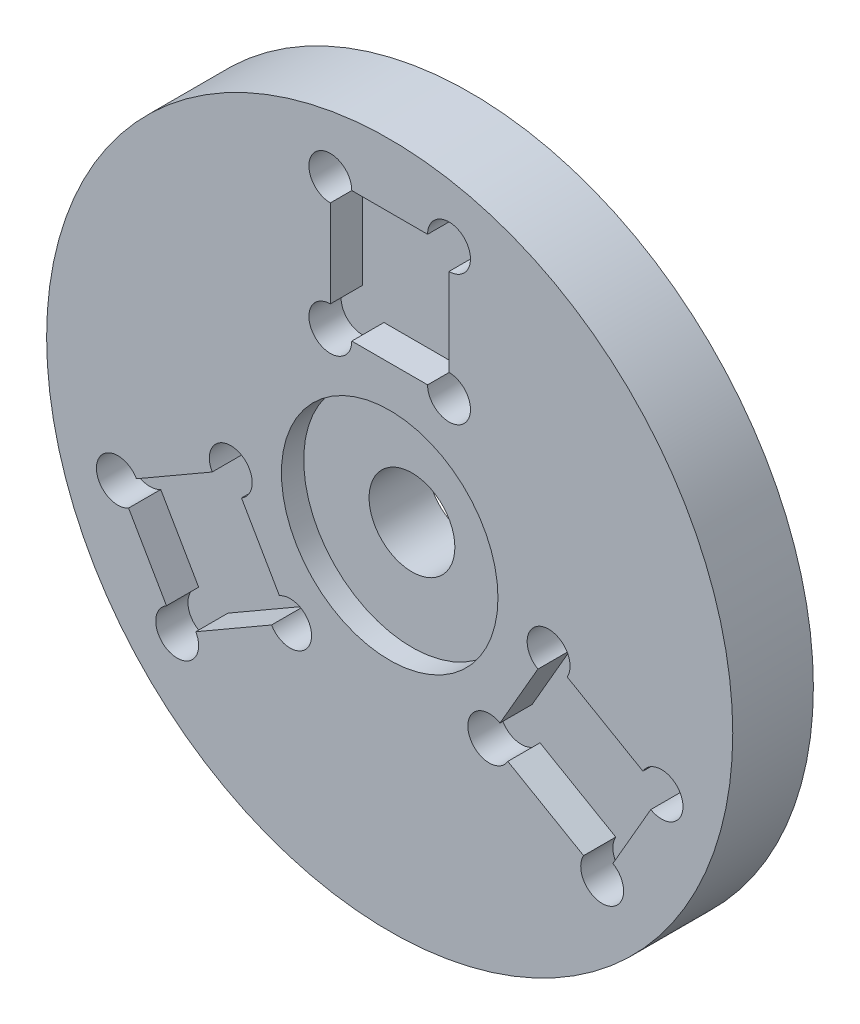
SolidWorks part; units mm, degrees
ref_plane "Front Plane" through (0, 0, 0) normal (0, 0, 1) x (1, 0, 0)
ref_plane "Top Plane" through (0, 0, 0) normal (0, 1, 0) x (1, 0, 0)
ref_plane "Right Plane" through (0, 0, 0) normal (1, 0, 0) x (0, 0, -1)
sketch "Sketch1" plane through (0, 0, 0) normal (0, 0, 1) x (1, 0, 0)
  circle A0 centre (0, 0) radius 50.8
  dimension "D1" = 101.6
extrude "baseplate" add sketch "Sketch1" along normal blind 11.938
sketch "coupling_circle" plane through (0, 0, 11.938) normal (0, 0, 1) x (1, 0, 0)
  circle A0 centre (0, 0) radius 31.75
  dimension "D1" = 63.5
sketch "Sketch3" plane through (0, 0, 11.938) normal (0, 0, 1) x (1, 0, 0)
  circle A0 centre (0, 0) radius 16.0337
  dimension "D1" = 32.0675
extrude "magnet_inset" cut sketch "Sketch3" against normal blind 3.302
sketch "Sketch4" plane through (0, 0, 11.938) normal (0, 0, 1) x (1, 0, 0)
  line L1 (-8.7877, 41.402) -> (8.7877, 41.402)
  line L2 (-8.7877, 41.402) -> (-8.7877, 22.098)
  line L3 (-8.7877, 22.098) -> (8.7877, 22.098)
  line L4 (8.7877, 41.402) -> (8.7877, 22.098)
  line L5 (-8.7877, 41.402) -> (8.7877, 22.098) construction
  line L6 (-8.7877, 22.098) -> (8.7877, 41.402) construction
  circle A0 centre (0, 0) radius 31.75 construction
  point P0 (0, 31.75)
  dimension "D1" = 19.304
  dimension "D2" = 17.5753
extrude "dowel_slot" cut sketch "Sketch4" against normal blind 4.7625
sketch "Sketch6" plane through (0, 0, 11.938) normal (0, 0, 1) x (1, 0, 0)
  circle A0 centre (-8.7877, 41.402) radius 3.175
  circle A1 centre (8.7877, 41.402) radius 3.175
  circle A2 centre (8.7877, 22.098) radius 3.175
  circle A3 centre (-8.7877, 22.098) radius 3.175
  dimension "D1" = 6.35
extrude "dowel_slot_reliefs" cut sketch "Sketch6" against normal up to surface (4.7625 mm away) up to face at (0, 31.75, 7.1755)
pattern_circular "dowel_slot_pattern" count 3 over 360 about axis through (0, 0, 0) along (0, 0, 1) of "dowel_slot", "dowel_slot_reliefs"
sketch "Sketch7" plane through (0, 0, 11.938) normal (0, 0, 1) x (1, 0, 0)
  circle A0 centre (0, 0) radius 6.35
  dimension "D1" = 12.7
extrude "central_hole" cut sketch "Sketch7" against normal through all
equation "\"plate_diam\"= 4"
equation "\"magnet_thickness\"= 0.125"
equation "\"coupling_diam\"= 2.5"
equation "\"ball_diam\"= .375"
equation "\"dowel_diam\"= 0.25"
equation "\"plate_thickness\"= 0.47"
equation "\"D1@Sketch1\"=\"plate_diam\""
equation "\"D1@baseplate\" = \"plate_thickness\""
equation "\"magnet_diam\"=1.26"
equation "\"D1@Sketch3\"=\"magnet_diam\"+\"magnet_radial_tol\""
equation "\"D1@magnet_inset\" = \"magnet_thickness\" + \"glue_thickness\""
equation "\"glue_thickness\"= 0.005"
equation "\"magnet_radial_tol\"= 0.0025"
equation "\"dowel_length\"= .75"
equation "\"D1@Sketch4\"=\"dowel_length\"+0.01"
equation "\"dowel_center_to_center\" = 2 * ( sqr ( ( ( ( \"dowel_diam\" + \"ball_diam\" ) / 2 ) ^ 2 ) / 2 ) )"
equation "\"dowel_slot_width\"= \"dowel_center_to_center\" + \"dowel_diam\""
equation "\"D2@Sketch4\"=\"dowel_slot_width\""
equation "\"D1@coupling_circle\" = \"coupling_diam\""
equation "\"dowel_slot_depth\" = \"dowel_diam\" * 0.75"
equation "\"D1@dowel_slot\" = \"dowel_slot_depth\""
equation "\"corner_relief_diam\"= 0.25"
equation "\"D1@Sketch6\"=\"corner_relief_diam\""
equation "\"central_hole_diam\"= 0.5"
equation "\"D1@Sketch7\"=\"central_hole_diam\""
equation "\"ball_center_to_slot_bottom\"= ( \"dowel_center_to_center\" / 2 ) + ( \"dowel_diam\" / 2 )"
equation "\"total_coupling_height\"= 1"
equation "\"ball_embed_depth\"= 0.15"
equation "\"ball_hole_diam\"= 2 * sqr ( ( \"ball_diam\" / 2 ) ^ 2 + - ( \"ball_diam\" / 2 - \"ball_embed_depth\" ) ^ 2 )"
equation "\"total_stack_height\"= \"plate_thickness\" - \"dowel_slot_depth\" + \"ball_center_to_slot_bottom\" + ( \"ball_diam\" / 2 ) - \"ball_embed_depth\" + \"plate_thickness\""
